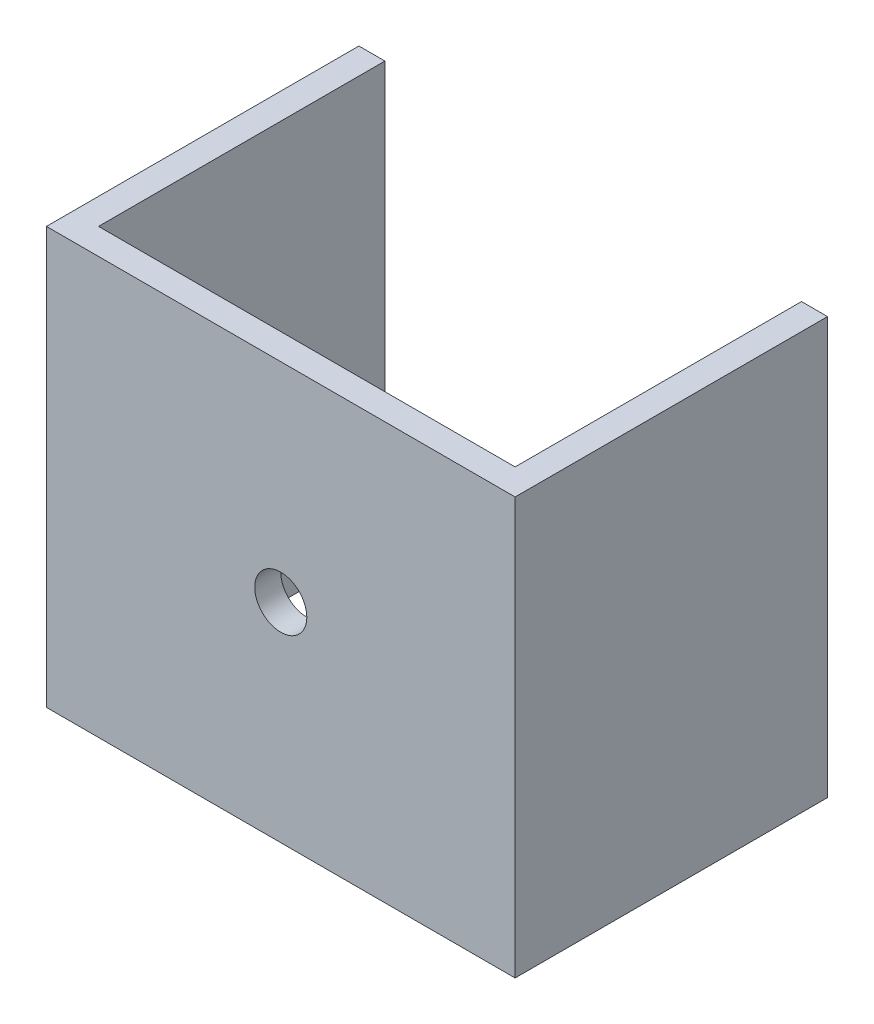
SolidWorks part; units mm, degrees
ref_plane "Front Plane" through (0, 0, 0) normal (0, 0, 1) x (1, 0, 0)
ref_plane "Top Plane" through (0, 0, 0) normal (0, 1, 0) x (1, 0, 0)
ref_plane "Right Plane" through (0, 0, 0) normal (1, 0, 0) x (0, 0, -1)
sketch "Sketch1" plane through (0, 0, 0) normal (0, 1, 0) x (1, 0, 0)
  line L0 (53.975, 38.1) -> (57.15, 38.1)
  line L1 (0, 0) -> (57.15, 0)
  line L2 (0, 0) -> (0, 38.1)
  line L3 (0, 38.1) -> (3.175, 38.1)
  line L4 (57.15, 0) -> (57.15, 38.1)
  line L6 (3.175, 38.1) -> (3.175, 3.175)
  line L7 (3.175, 3.175) -> (53.975, 3.175)
  line L8 (53.975, 38.1) -> (53.975, 3.175)
  dimension "D1" = 57.15
  dimension "D2" = 38.1
  dimension "D3" = 3.175
  dimension "D4" = 3.175
  dimension "D5" = 3.175
extrude "Boss-Extrude1" add sketch "Sketch1" along normal blind 50.8
sketch "Sketch2" plane through (0, 0, 0) normal (0, 0, 1) x (1, 0, 0)
  line L0 (-1000, 25.4) -> (49000, 25.4) construction
  line L1 (0, 50.8) -> (0, 0) construction
  line L2 (28.575, -1000) -> (28.575, 49000) construction
  line L3 (0, 0) -> (57.15, 0) construction
  circle A0 centre (28.575, 25.4) radius 3.175
  point P5 (0, 25.4)
  point P10 (28.575, 0)
  point P12 (0, 0)
  dimension "D1" = 6.35
extrude "Cut-Extrude1" cut sketch "Sketch2" against normal through all
